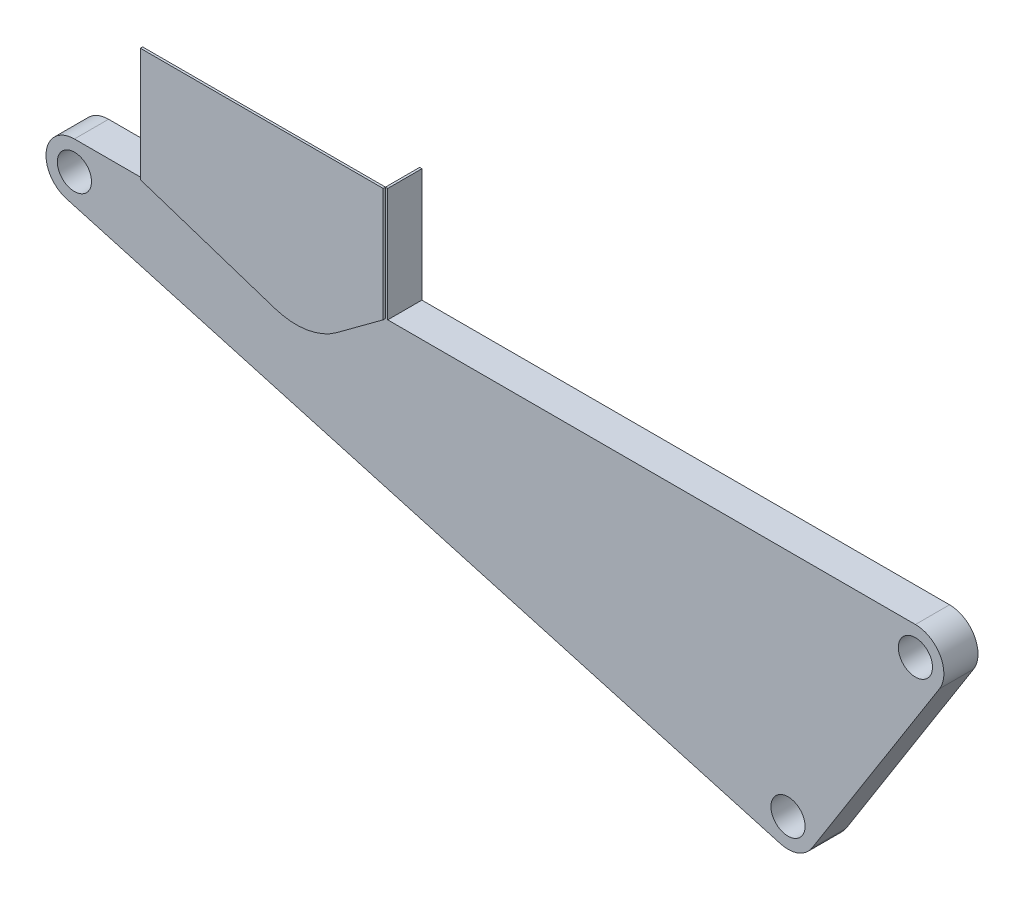
SolidWorks part; units mm, degrees
ref_plane "前基準面" through (0, 0, 0) normal (0, 0, 1) x (1, 0, 0)
ref_plane "上基準面" through (0, 0, 0) normal (0, 1, 0) x (1, 0, 0)
ref_plane "右基準面" through (0, 0, 0) normal (1, 0, 0) x (0, 0, -1)
sketch "草圖1" plane through (0, 0, 0) normal (0, 0, 1) x (1, 0, 0)
  line L0 (0, 0) -> (36.94, 0) construction
  line L1 (36.94, 0) -> (31.3447, -8.8495) construction
  line L2 (31.3447, -8.8495) -> (0, 0) construction
  line L3 (0, 1.25) -> (36.94, 1.25)
  line L4 (-0.3396, -1.203) -> (31.0051, -10.0525)
  line L5 (36.94, 0) -> (37.9965, -0.668) construction
  line L6 (37.9965, -0.668) -> (32.4012, -9.5175)
  arc A0 (0, 1.25) -> (-0.3396, -1.203) centre (0, 0) ccw
  arc A1 (37.9965, -0.668) -> (36.94, 1.25) centre (36.94, 0) ccw
  arc A2 (31.0051, -10.0525) -> (32.4012, -9.5175) centre (31.3447, -8.8495) ccw
  circle A3 centre (0, 0) radius 0.75
  circle A4 centre (36.94, 0) radius 0.75
  circle A5 centre (31.3447, -8.8495) radius 0.75
  dimension "D1" = 2.5
  dimension "D5" = 1.5
  dimension "D6" = 2.5
  dimension "D2" = 32.57
  dimension "D3" = 36.94
  dimension "D4" = 10.47
extrude "填料-伸長1" add sketch "草圖1" along normal mid plane 1.5 contours L3 A1 L6 A2 L4 A0
sketch "草圖2" plane through (0, 0, 0.75) normal (0, 0, 1) x (1, 0, 0)
  circle A0 centre (31.3447, -8.8495) radius 0.75 construction
  circle A1 centre (36.94, 0) radius 0.75 construction
  circle A2 centre (0, 0) radius 0.75 construction
  circle A3 centre (31.3447, -8.8495) radius 0.75
  circle A4 centre (36.94, 0) radius 0.75
  circle A5 centre (0, 0) radius 0.75
extrude "除料-伸長1" cut sketch "草圖2" against normal blind 11.5
sketch "草圖3" plane through (0, 0, 0.75) normal (0, 0, 1) x (1, 0, 0)
  line L0 (2.9925, 1.25) -> (8.9009, -0.6933)
  line L1 (0, 1.25) -> (36.94, 1.25) construction
  line L2 (11.6195, -0.2574) -> (13.6623, 1.25)
  line L3 (13.6623, 1.25) -> (2.9925, 1.25)
  arc A0 (8.9009, -0.6933) -> (11.6195, -0.2574) centre (9.8382, 2.1565) ccw
  dimension "D1" = 3
extrude "除料-伸長2" cut sketch "草圖3" against normal blind 10
sketch "草圖5" plane through (0, 1.25, 0) normal (0, 1, 0) x (1, 0, 0)
  line L0 (13.6623, 0.75) -> (36.94, 0.75) construction
  line L1 (13.6623, -0.75) -> (13.7623, -0.75)
  line L2 (13.6623, -0.75) -> (13.6623, 0.75)
  line L3 (13.6623, 0.75) -> (13.7623, 0.75)
  line L4 (13.7623, -0.75) -> (13.7623, 0.75)
  dimension "D1" = 0.1
extrude "填料-伸長3" add sketch "草圖5" along normal blind 5
sketch "草圖6" plane through (0, 0, 0.75) normal (0, 0, 1) x (1, 0, 0)
  line L0 (2.9925, 1.25) -> (8.9009, -0.6933) construction
  line L1 (13.6623, 6.25) -> (13.6623, 1.25) construction
  line L2 (11.6195, -0.2574) -> (13.6623, 1.25) construction
  line L3 (13.6623, 6.25) -> (13.6623, 1.25)
  line L4 (2.9925, 1.25) -> (8.9009, -0.6933)
  line L5 (11.6195, -0.2574) -> (13.6623, 1.25)
  line L6 (2.9925, 1.25) -> (2.9925, 6.25)
  line L7 (2.9925, 6.25) -> (13.6623, 6.25)
  arc A1 (8.9009, -0.6933) -> (11.6195, -0.2574) centre (9.8382, 2.1565) ccw construction
  arc A2 (8.9009, -0.6933) -> (11.6195, -0.2574) centre (9.8382, 2.1565) ccw
extrude "填料-伸長4" add sketch "草圖6" along normal blind 0.1 separate body
